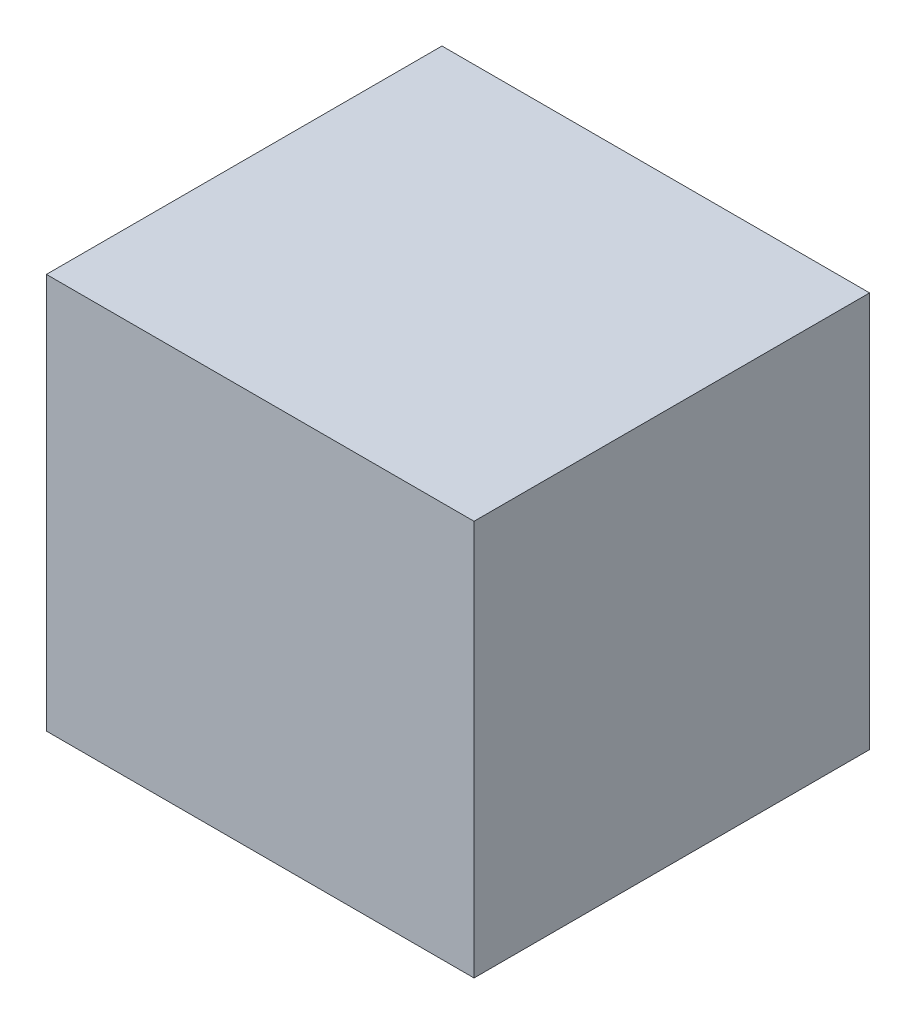
SolidWorks part; units mm, degrees
ref_plane "Front Plane" through (0, 0, 0) normal (0, 0, 1) x (1, 0, 0)
ref_plane "Top Plane" through (0, 0, 0) normal (0, 1, 0) x (1, 0, 0)
ref_plane "Right Plane" through (0, 0, 0) normal (1, 0, 0) x (0, 0, -1)
other "Configuration Table"
sketch "Sketch1" plane through (0, 0, 0) normal (0, 0, 1) x (1, 0, 0)
  line L1 (8, -18.5) -> (48, -18.5)
  line L2 (8, -18.5) -> (8, 18.5)
  line L3 (8, 18.5) -> (48, 18.5)
  line L4 (48, -18.5) -> (48, 18.5)
extrude "MTG_reduktor_govde_37x37x40_1" add sketch "Sketch1" against normal blind 37 from offset 18.5 separate body
